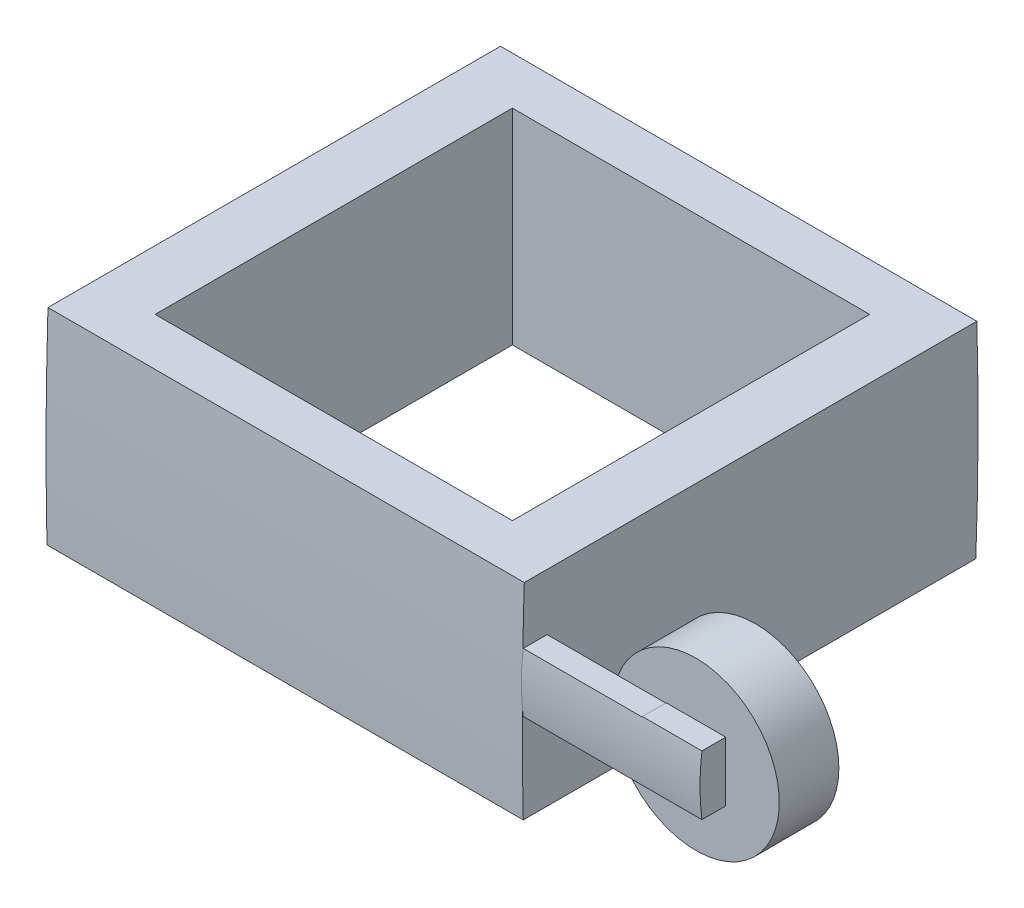
SolidWorks part; units mm, degrees
ref_plane "Front Plane" through (0, 0, 0) normal (0, 0, 1) x (1, 0, 0)
ref_plane "Top Plane" through (0, 0, 0) normal (0, 1, 0) x (1, 0, 0)
ref_plane "Right Plane" through (0, 0, 0) normal (1, 0, 0) x (0, 0, -1)
sketch "Sketch1" plane through (0, 0, 0) normal (0, 0, 1) x (1, 0, 0)
  circle A0 centre (0, 0) radius 14
  circle A1 centre (0, 0) radius 10
  circle A2 centre (0, 0) radius 5.5
extrude "Boss-Extrude1" add sketch "Sketch1" along normal blind 10 contours A0
sketch "Sketch2" plane through (0, 0, 0) normal (0, 0, -1) x (-1, 0, 0)
  circle A0 centre (0, 0) radius 2.25
extrude "Cut-Extrude1" cut sketch "Sketch2" against normal blind 5
sketch "Sketch3" plane through (0, 0, 0) normal (0, 0, -1) x (-1, 0, 0)
  circle A0 centre (0, 0) radius 5
extrude "Cut-Extrude2" cut sketch "Sketch3" against normal blind 1.8
sketch "Sketch4" plane through (0, 0, 10) normal (0, 0, 1) x (1, 0, 0)
  line L1 (-5, 5) -> (5, 5)
  line L2 (-5, 5) -> (-5, -5)
  line L3 (-5, -5) -> (5, -5)
  line L4 (5, 5) -> (5, -5)
  line L5 (-5, 5) -> (5, -5) construction
  line L6 (-5, -5) -> (5, 5) construction
  point P0 (0, 0)
  dimension "D1" = 10
  dimension "D2" = 10
extrude "Boss-Extrude2" add sketch "Sketch4" along normal blind 8
sketch "Sketch6" plane through (-5, 0, 0) normal (-1, 0, 0) x (0, 0, 1)
  line L0 (10, 5) -> (10, -5) construction
  line L1 (10, 4.9129) -> (18, 4.9129)
  line L2 (10, 4.9129) -> (10, -5)
  line L3 (10, -5) -> (18, -5)
  line L4 (18, 4.9129) -> (18, -5)
extrude "Boss-Extrude3" add sketch "Sketch6" along normal blind 20
sketch "Sketch7" plane through (5, 0, 0) normal (1, 0, 0) x (0, 0, -1)
  line L0 (-18, 5) -> (-18, -5)
  line L1 (-18, -5) -> (-14, -5)
  line L2 (-18, -5) -> (-10, -5) construction
  line L3 (-18, 5) -> (-14, 5)
  line L4 (-18, 5) -> (-10, 5) construction
  arc A2 (-14, -5) -> (-14, 5) centre (23.6696, 0) cw
extrude "Cut-Extrude3" cut sketch "Sketch7" against normal blind 30
sketch "Sketch8" plane through (-25, 0, 0) normal (-1, 0, 0) x (0, 0, 1)
  line L4 (-62.1689, 14.4036) -> (13.8311, 14.4036)
  line L5 (-62, -20.0436) -> (14, -20.0436)
  arc A0 (13.8311, 14.4036) -> (14, -20.0436) centre (-602.0691, -5.8394) cw
  arc A1 (-62, -20.0436) -> (-62.1689, 14.4036) centre (468.3236, -0.2201) cw
  dimension "D1" = 76
  dimension "D2" = 76
extrude "Boss-Extrude4" add sketch "Sketch8" along normal blind 80
sketch "Sketch9" plane through (0, 14.4036, 0) normal (0, 1, 0) x (1, 0, 0)
  line L1 (-35, -5.8311) -> (-95, -5.8311)
  line L2 (-35, -5.8311) -> (-35, 54.1689)
  line L3 (-35, 54.1689) -> (-95, 54.1689)
  line L4 (-95, -5.8311) -> (-95, 54.1689)
  line L5 (-35, -5.8311) -> (-95, 54.1689) construction
  line L6 (-35, 54.1689) -> (-95, -5.8311) construction
  point P0 (-65, 24.1689)
extrude "Cut-Extrude4" cut sketch "Sketch9" against normal blind 100
